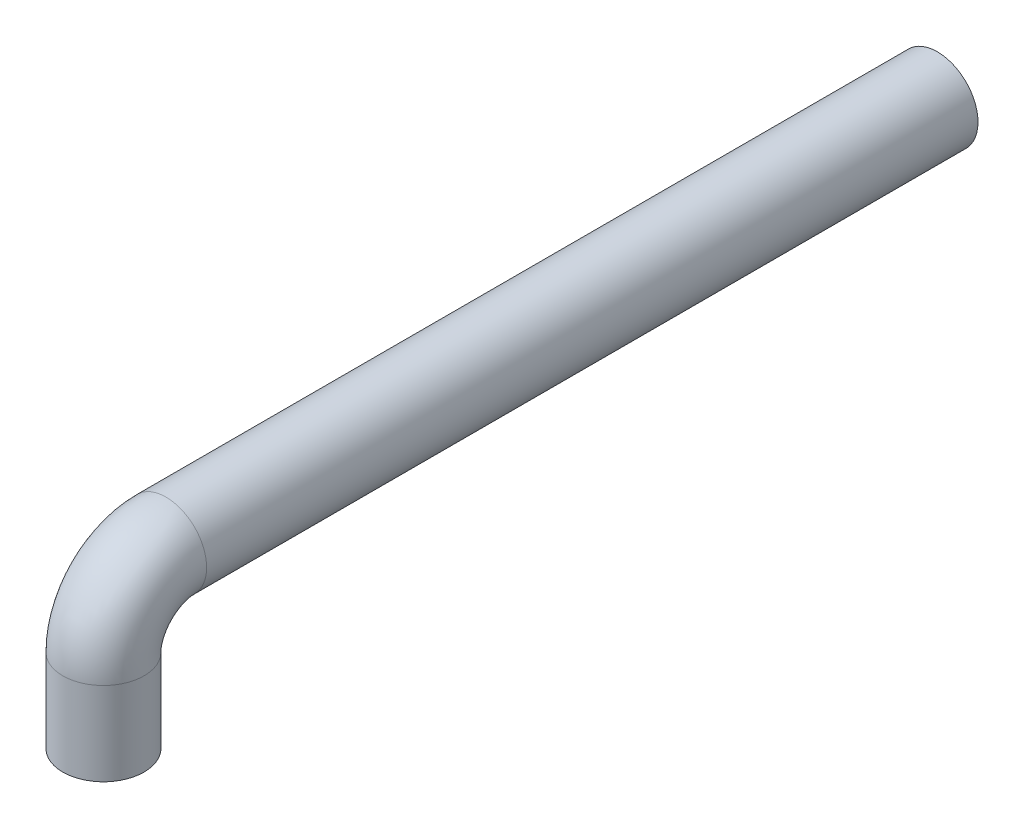
SolidWorks part; units mm, degrees
material "Alloy Steel"
ref_plane "Front Plane" through (0, 0, 0) normal (0, 0, 1) x (1, 0, 0)
ref_plane "Top Plane" through (0, 0, 0) normal (0, 1, 0) x (1, 0, 0)
ref_plane "Right Plane" through (0, 0, 0) normal (1, 0, 0) x (0, 0, -1)
sketch "Sketch2" plane through (0, 0, 0) normal (0, 0, 1) x (1, 0, 0)
  circle A0 centre (0, 0) radius 4.953
  dimension "D1" = 9.906
ref_plane "Plane1" through (0, -17.78, 0) normal (0, 1, 0) x (1, 0, 0)
sketch "Sketch3" plane through (0, -17.78, 0) normal (0, 1, 0) x (1, 0, 0)
  circle A0 centre (0, -101.6) radius 4.953
  dimension "D1" = 9.906
  dimension "D2" = 101.6
sketch "Sketch4" plane through (0, 0, 0) normal (1, 0, 0) x (0, 0, -1)
  line L0 (-101.6, -17.78) -> (-101.6, -7.62)
  line L1 (-96.647, -17.78) -> (-106.553, -17.78) construction
  line L2 (-93.98, 0) -> (0, 0)
  arc A0 (-101.6, -7.62) -> (-93.98, 0) centre (-93.98, -7.62) cw
  dimension "D1" = 7.62
sweep "Sweep1" add profiles "Sketch2" path "Sketch4"
